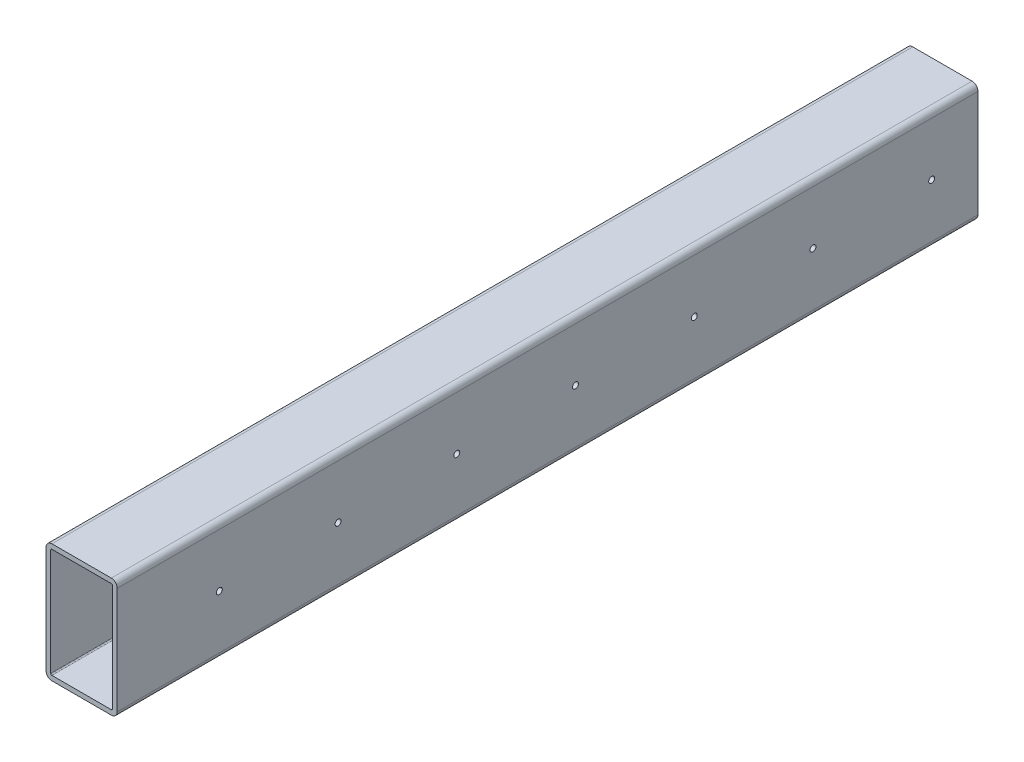
SolidWorks part; units mm, degrees
ref_plane "Front Plane" through (0, 0, 0) normal (0, 0, 1) x (1, 0, 0)
ref_plane "Top Plane" through (0, 0, 0) normal (0, 1, 0) x (1, 0, 0)
ref_plane "Right Plane" through (0, 0, 0) normal (1, 0, 0) x (0, 0, -1)
sketch "Sketch2" plane through (0, 0, 0) normal (1, 0, 0) x (0, 0, -1)
  line L0 (725, 0) -> (-725, 0)
  point P4 (0, 0)
  dimension "D1" = 1450
other "Tube square TS3X3X0.3125(1)"
ref_plane "Plane1" through (0, 0, -725) normal (0, 0, 1) x (0, -1, 0)
sketch "Sketch1" plane through (0, 0, -725) normal (0, 0, 1) x (0, -1, 0)
  line L0 (-90, -52) -> (90, -52)
  line L1 (-92, -50) -> (-92, 50)
  line L2 (90, 52) -> (-90, 52)
  line L3 (92, 50) -> (92, -50)
  line L4 (-90, -60) -> (90, -60)
  line L5 (-100, -50) -> (-100, 50)
  line L6 (90, 60) -> (-90, 60)
  line L7 (100, 50) -> (100, -50)
  line L8 (-100, 0) -> (-92, 0) construction
  line L9 (-92, 0) -> (92, 0) construction
  line L10 (92, 0) -> (100, 0) construction
  line L11 (0, 60) -> (0, 52) construction
  line L12 (0, 52) -> (0, -52) construction
  line L13 (0, -52) -> (0, -60) construction
  arc A0 (100, 50) -> (90, 60) centre (90, 50) ccw
  arc A1 (90, -60) -> (100, -50) centre (90, -50) ccw
  arc A2 (-100, -50) -> (-90, -60) centre (-90, -50) ccw
  arc A3 (-90, 60) -> (-100, 50) centre (-90, 50) ccw
  arc A4 (-90, 52) -> (-92, 50) centre (-90, 50) ccw
  arc A5 (92, 50) -> (90, 52) centre (90, 50) ccw
  arc A6 (90, -52) -> (92, -50) centre (90, -50) ccw
  arc A7 (-92, -50) -> (-90, -52) centre (-90, -50) ccw
  point P6 (-100, -60)
  point P33 (-100, 60)
  point P35 (100, 60)
  point P36 (100, -60)
  point P37 (0, 0)
  point P38 (0, 0)
  dimension "D1" = 10
  dimension "Thickness" = 8
  dimension "V_leg" = 120
  dimension "H_leg" = 200
sketch "Sketch3" plane through (60, 0, 0) normal (1, 0, 0) x (0, 0, -1)
  line L0 (725, 0) -> (-725, 0) construction
  line L1 (-725, -90) -> (-725, 90) construction
  point P0 (-553, 0)
  point P7 (-353, 0)
  point P8 (-153, 0)
  point P9 (47, 0)
  point P10 (247, 0)
  dimension "D1" = 172
  dimension "D2" = 5
sketch "Sketch7" plane through (60, 0, 0) normal (1, 0, 0) x (0, 0, -1)
  line L0 (725, -90) -> (725, 90) construction
  line L1 (725, 0) -> (647, 0) construction
  circle A0 centre (647, 0) radius 5
  circle A1 centre (447, 0) radius 5
  circle A2 centre (247, 0) radius 5
  circle A3 centre (47, 0) radius 5
  circle A4 centre (-153, 0) radius 5
  circle A5 centre (-353, 0) radius 5
  circle A6 centre (-553, 0) radius 5
  dimension "D3" = 10
  dimension "D1" = 78
  dimension "D2" = 7
extrude "Cut-Extrude1" cut sketch "Sketch7" against normal through all
